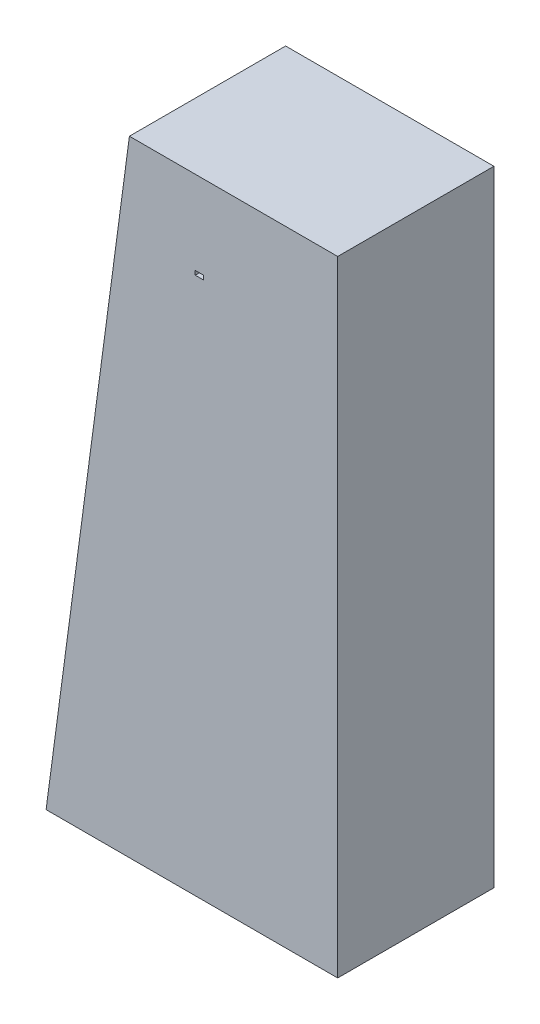
SolidWorks part; units mm, degrees
ref_plane "Front Plane" through (0, 0, 0) normal (0, 0, 1) x (1, 0, 0)
ref_plane "Top Plane" through (0, 0, 0) normal (0, 1, 0) x (1, 0, 0)
ref_plane "Right Plane" through (0, 0, 0) normal (1, 0, 0) x (0, 0, -1)
sketch "Sketch1" plane through (0, 0, 0) normal (0, 0, 1) x (1, 0, 0)
  line L0 (0, 0) -> (70, 0)
  line L1 (0, 0) -> (20, 150)
  line L2 (20, 150) -> (70, 150)
  line L3 (70, 150) -> (70, 0)
  dimension "D1" = 150
  dimension "D2" = 70
  dimension "D3" = 50
extrude "Boss-Extrude2" add sketch "Sketch1" along normal mid plane 37.5 contours L3 L0 L1 L2
sketch "Sketch2" plane through (0, 0, -18.75) normal (0, 0, -1) x (-1, 0, 0)
  line L0 (-36.8, 150) -> (-36.8, 0) construction
  line L1 (-20, 150) -> (-70, 150) construction
  line L2 (0, 0) -> (-70, 0) construction
  line L4 (-38.3, 130) -> (-35.3, 130)
  line L5 (-38.3, 130) -> (-38.3, 129)
  line L6 (-38.3, 129) -> (-35.3, 129)
  line L7 (-35.3, 130) -> (-35.3, 129)
  line L8 (-38.3, 130) -> (-35.3, 129) construction
  line L9 (-38.3, 129) -> (-35.3, 130) construction
  line L10 (-70, 150) -> (-70, 0) construction
  point P6 (-36.8, 129.5)
  dimension "D1" = 20
  dimension "D2" = 1
  dimension "D3" = 3
  dimension "D4" = 33.2
extrude "Cut-Extrude1" cut sketch "Sketch2" against normal blind 5
sketch "Sketch3" plane through (0, 0, 18.75) normal (0, 0, 1) x (1, 0, 0)
  line L1 (20, 150) -> (70, 150) construction
  line L2 (35.8, 130) -> (37.8, 130)
  line L3 (35.8, 130) -> (35.8, 129)
  line L4 (35.8, 129) -> (37.8, 129)
  line L5 (37.8, 130) -> (37.8, 129)
  line L6 (35.8, 130) -> (37.8, 129) construction
  line L7 (35.8, 129) -> (37.8, 130) construction
  line L9 (36.8, 150) -> (36.8, 0) construction
  line L12 (70, 150) -> (70, 0) construction
  point P2 (36.8, 129.5)
  dimension "D1" = 20
  dimension "D2" = 33.2
  dimension "D3" = 2
  dimension "D4" = 1
extrude "Cut-Extrude2" cut sketch "Sketch3" against normal blind 5
